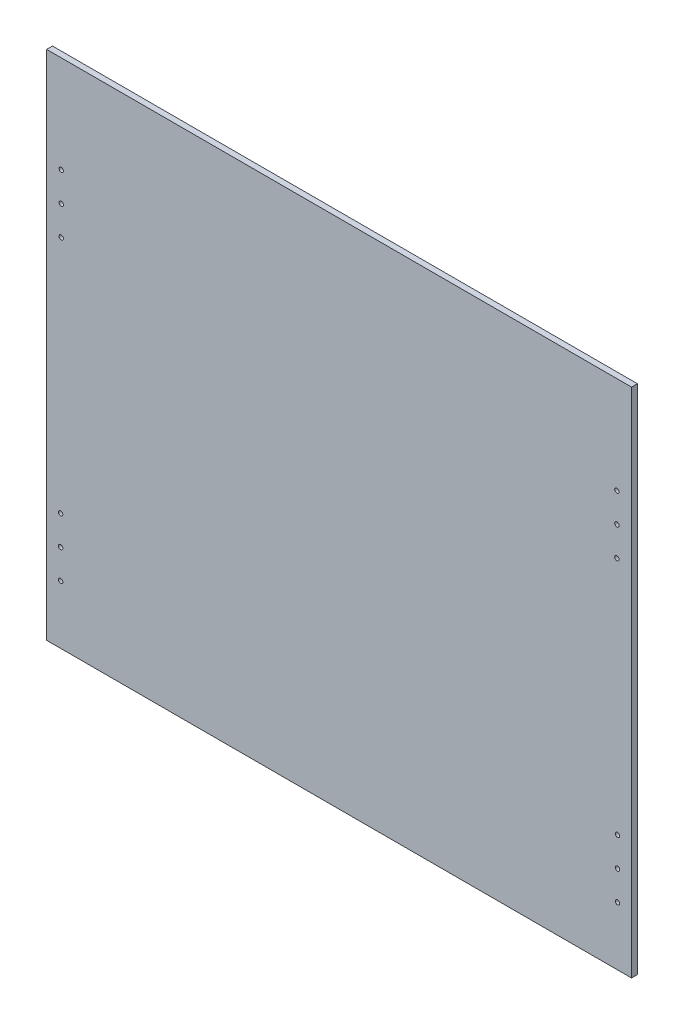
SolidWorks part; units mm, degrees
material "Oak"
ref_plane "Front Plane" through (0, 0, 0) normal (0, 0, 1) x (1, 0, 0)
ref_plane "Top Plane" through (0, 0, 0) normal (0, 1, 0) x (1, 0, 0)
ref_plane "Right Plane" through (0, 0, 0) normal (1, 0, 0) x (0, 0, -1)
sketch "Sketch1" plane through (0, 0, 0) normal (0, 0, 1) x (1, 0, 0)
  line L1 (-200, 175) -> (200, 175)
  line L2 (-200, 175) -> (-200, -175)
  line L3 (-200, -175) -> (200, -175)
  line L4 (200, 175) -> (200, -175)
  circle A0 centre (190.4202, -135) radius 1.5
  circle A1 centre (190.4202, -115) radius 1.5
  circle A2 centre (190.4202, -95) radius 1.5
  circle A3 centre (190, 68.62) radius 1.5
  circle A5 centre (190, 88.62) radius 1.5
  circle A6 centre (190, 108.62) radius 1.5
  circle A7 centre (-190.4202, -135) radius 1.5
  circle A8 centre (-190.4202, -95) radius 1.5
  circle A9 centre (-190.4202, -115) radius 1.5
  circle A10 centre (-190, 68.62) radius 1.5
  circle A11 centre (-190, 88.62) radius 1.5
  circle A12 centre (-190, 108.62) radius 1.5
  point P0 (0, 0)
  dimension "D1" = 400
  dimension "D2" = 350
  dimension "D10" = 10
  dimension "D6" = 3
  dimension "D11" = 3
extrude "Boss-Extrude1" add sketch "Sketch1" along normal blind 4
